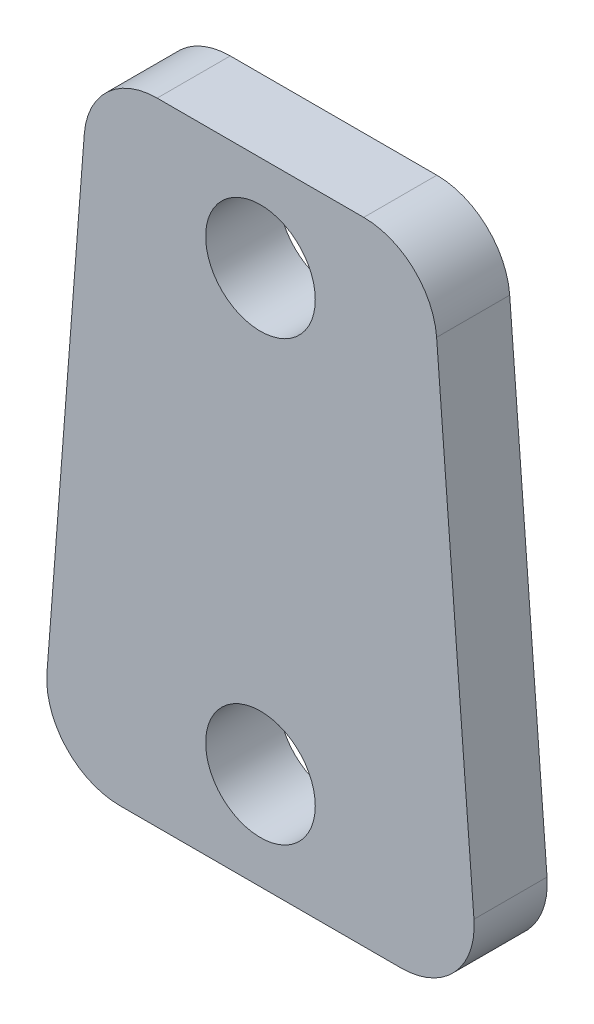
SolidWorks part; units mm, degrees
ref_plane "Front Plane" through (0, 0, 0) normal (0, 0, 1) x (1, 0, 0)
ref_plane "Top Plane" through (0, 0, 0) normal (0, 1, 0) x (1, 0, 0)
ref_plane "Right Plane" through (0, 0, 0) normal (1, 0, 0) x (0, 0, -1)
sketch "Sketch1" plane through (0, 0, 0) normal (0, 0, 1) x (1, 0, 0)
  line L4 (7.6534, 106.8812) -> (9.2751, 85.7992)
  line L7 (-6.1094, 82.3807) -> (6.1094, 82.3807)
  line L8 (-4.4877, 109.8127) -> (4.4877, 109.8127)
  line L9 (0, 82.3807) -> (0, 109.8127)
  line L10 (-9.2751, 85.7992) -> (-7.6534, 106.8812)
  circle A0 centre (0, 105.664) radius 2.3812
  circle A1 centre (0, 86.614) radius 2.3812
  arc A2 (-9.2751, 85.7992) -> (-6.1094, 82.3807) centre (-6.1094, 85.5557) ccw
  arc A3 (9.2751, 85.7992) -> (6.1094, 82.3807) centre (6.1094, 85.5557) cw
  arc A4 (7.6534, 106.8812) -> (4.4877, 109.8127) centre (4.4877, 106.6377) ccw
  arc A5 (-4.4877, 109.8127) -> (-7.6534, 106.8812) centre (-4.4877, 106.6377) ccw
  dimension "D1" = 19.05
  dimension "D2" = 4.2333
  dimension "D3" = 4.7625
  dimension "D4" = 4.7625
  dimension "D5" = 3.175
extrude "Boss-Extrude1" add sketch "Sketch1" along normal blind 3.175 contours L8 A5 L10 A2 L7 L9 A1 A0 | L4 A4 L8 L9 A0 A1 L7 A3
